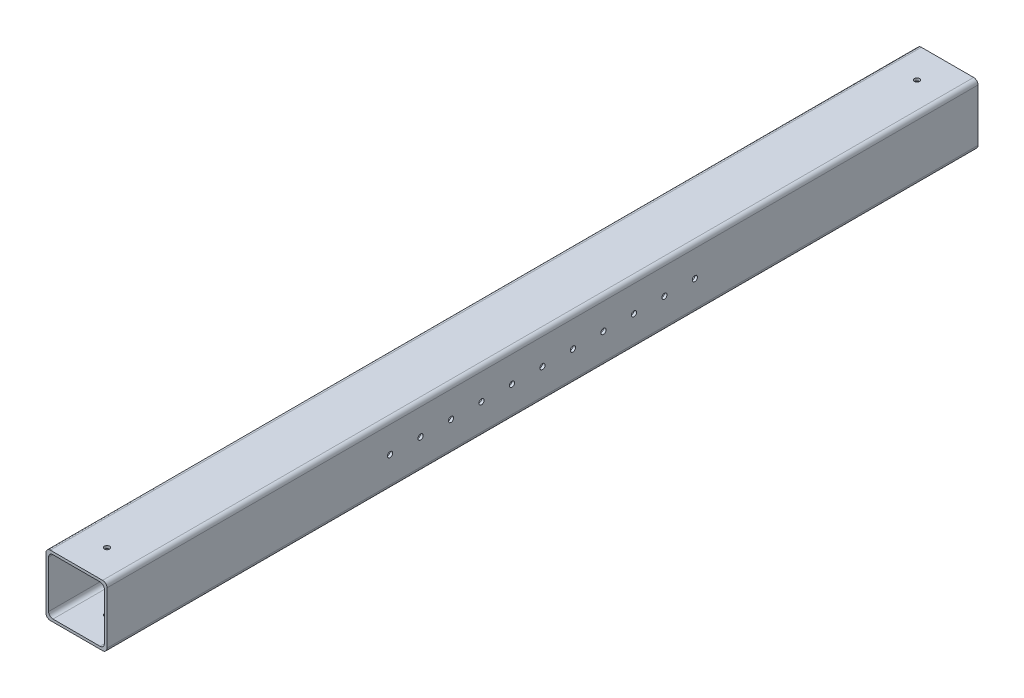
SolidWorks part; units mm, degrees
ref_plane "Front Plane" through (0, 0, 0) normal (0, 0, 1) x (1, 0, 0)
ref_plane "Top Plane" through (0, 0, 0) normal (0, 1, 0) x (1, 0, 0)
ref_plane "Right Plane" through (0, 0, 0) normal (1, 0, 0) x (0, 0, -1)
sketch "Sketch1" plane through (0, 0, 0) normal (0, 0, 1) x (1, 0, 0)
  line L0 (3, 67) -> (67, 67)
  line L1 (0, 0) -> (70, 0)
  line L2 (0, 0) -> (0, 70)
  line L3 (0, 70) -> (70, 70)
  line L4 (70, 0) -> (70, 70)
  line L5 (67, 3) -> (67, 67)
  line L6 (3, 3) -> (67, 3)
  line L7 (3, 3) -> (3, 67)
  dimension "D1" = 70
  dimension "D2" = 70
  dimension "D3" = 3
extrude "Boss-Extrude1" add sketch "Sketch1" along normal blind 1000
fillet "Fillet1" radius 5 8 edges at (67, 67, 500) (0, 70, 500) (0, 0, 500) (67, 3, 500) (70, 0, 500) (3, 3, 500) (3, 67, 500) (70, 70, 500)
sketch "Sketch2" plane through (0, 70, 0) normal (0, 1, 0) x (1, 0, 0)
  line L0 (35, 0) -> (35, -1000) construction
  line L1 (65, 0) -> (5, 0) construction
  line L2 (65, -1000) -> (5, -1000) construction
  circle A0 centre (35, -965) radius 3
  circle A1 centre (35, -35) radius 3
  dimension "D1" = 6
  dimension "D3" = 6
  dimension "D2" = 35
  dimension "D4" = 35
extrude "Cut-Extrude1" cut sketch "Sketch2" against normal blind 70
sketch "Sketch3" plane through (70, 0, 0) normal (1, 0, 0) x (0, 0, -1)
  line L0 (-1000, 70) -> (0, 70) construction
  line L2 (-1000, 5) -> (-1000, 65) construction
  circle A0 centre (-500, 35) radius 3
  dimension "D3" = 6
  dimension "D1" = 35
  dimension "D2" = 500
extrude "Cut-Extrude2" cut sketch "Sketch3" against normal blind 70
pattern_linear "LPattern1" count 6 spacing 35 along (0, 0, -1) count 6 spacing 35 along (0, 0, 1) of "Cut-Extrude2"
